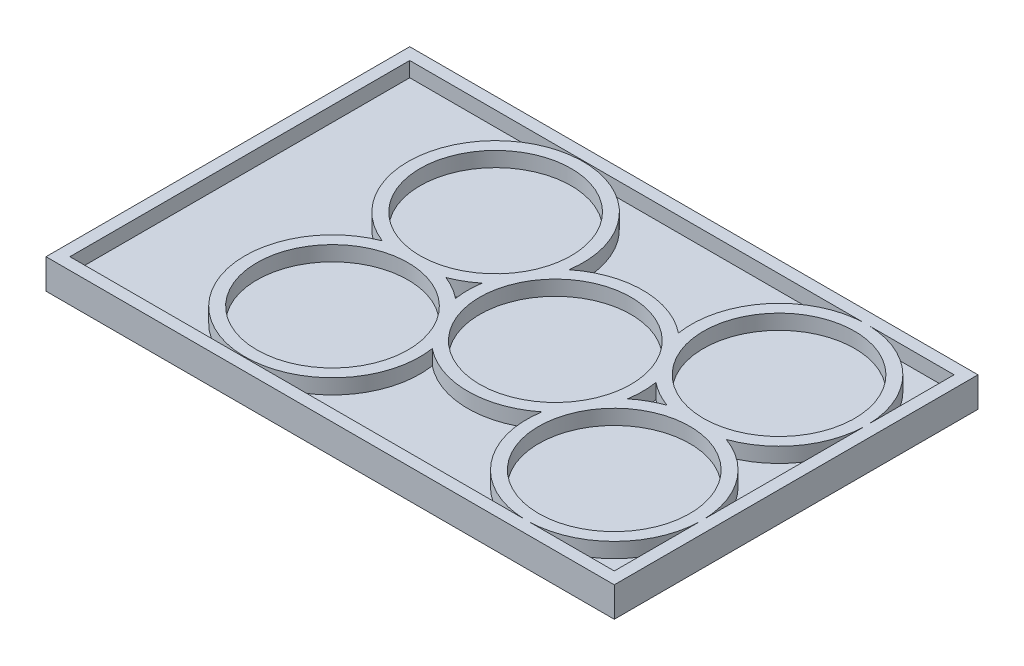
SolidWorks part; units mm, degrees
ref_plane "Front Plane" through (0, 0, 0) normal (0, 0, 1) x (1, 0, 0)
ref_plane "Top Plane" through (0, 0, 0) normal (0, 1, 0) x (1, 0, 0)
ref_plane "Right Plane" through (0, 0, 0) normal (1, 0, 0) x (0, 0, -1)
sketch "Sketch1" plane through (0, 0, 0) normal (0, 1, 0) x (1, 0, 0)
  line L1 (-43.2038, 39.7322) -> (32.8362, 39.7322)
  line L2 (-43.2038, 39.7322) -> (-43.2038, -8.9378)
  line L3 (-43.2038, -8.9378) -> (32.8362, -8.9378)
  line L4 (32.8362, 39.7322) -> (32.8362, -8.9378)
extrude "Boss-Extrude1" add sketch "Sketch1" along normal blind 2
sketch "Sketch2" plane through (0, 2, 0) normal (0, 1, 0) x (1, 0, 0)
  line L0 (32.8362, 39.7322) -> (32.8362, 26.4222)
  line L1 (32.8362, -8.9378) -> (32.8362, 39.7322) construction
  line L3 (32.8362, -8.9378) -> (32.8362, 4.3722)
  line L8 (-43.2038, 39.7322) -> (-43.2038, 38.1322)
  line L9 (-43.2038, 39.7322) -> (32.8362, 39.7322)
  line L10 (-43.2038, 39.7322) -> (-43.2038, -8.9378)
  line L11 (-43.2038, -8.9378) -> (32.8362, -8.9378)
  line L12 (32.8362, 39.7322) -> (32.8362, -8.9378)
  line L14 (32.8362, -8.9378) -> (31.2362, -8.9378)
  line L17 (31.2362, -7.3378) -> (-41.6038, -7.3378)
  line L18 (31.2362, -7.3378) -> (31.2362, 38.1322)
  line L19 (31.2362, 38.1322) -> (-41.6038, 38.1322)
  line L20 (-41.6038, -7.3378) -> (-41.6038, 38.1322)
  circle A0 centre (19.5262, 26.4222) radius 10.115
  circle A1 centre (19.5262, 26.4222) radius 11.715
  circle A2 centre (19.5262, 4.3722) radius 10.115
  circle A4 centre (0.6157, 15.3972) radius 10.115
  circle A5 centre (0.6157, 15.3972) radius 11.715
  circle A6 centre (-18.2897, 26.3122) radius 10.115
  circle A7 centre (-18.2897, 26.3122) radius 11.715
  circle A8 centre (-18.2897, 4.4822) radius 10.115
  circle A9 centre (-18.2897, 4.4822) radius 11.715
  circle A10 centre (19.5262, 4.3722) radius 11.715
extrude "Boss-Extrude5" add sketch "Sketch2" along normal blind 2 contours A9 A6 A5 A7 | A5 A7 | A9 A7 A5 A6 | A7 A9 | A5 A9 A7 A8 | A5 A9 | A9 A4 A7 A5 | A10 A5 A1 A7 A4 A9 | A1 A5 | A10 A1 L18 L19 A5 A0 | A1 A10 | L17 A10 L18 A1 A5 A2 | A5 A10 | A7 A9 A5 A8
sketch "Sketch3" plane through (0, 2, 0) normal (0, 1, 0) x (1, 0, 0)
  line L0 (-43.2038, 39.7322) -> (-41.6038, 39.7322)
  line L1 (-43.2038, 39.7322) -> (32.8362, 39.7322)
  line L2 (-43.2038, 39.7322) -> (-43.2038, -8.9378)
  line L3 (-43.2038, -8.9378) -> (32.8362, -8.9378)
  line L4 (32.8362, 39.7322) -> (32.8362, -8.9378)
  line L6 (32.8362, -8.9378) -> (31.2362, -8.9378)
  line L9 (-41.6038, 38.1322) -> (31.2362, 38.1322)
  line L10 (-41.6038, 38.1322) -> (-41.6038, -7.3378)
  line L11 (-41.6038, -7.3378) -> (31.2362, -7.3378)
  line L12 (31.2362, 38.1322) -> (31.2362, -7.3378)
  point P10 (0, 0)
  line M13 (31.2362, 4.7144) -> (31.2362, 4.0299)
  line M15 (19.8684, -7.3378) -> (19.1839, -7.3378)
  line M22 (19.1839, 38.1322) -> (19.8684, 38.1322)
  line M24 (31.2362, 26.7644) -> (31.2362, 26.0799)
  line M25 (-43.2038, 39.7322) -> (-43.2038, -8.9378)
  line M26 (-43.2038, -8.9378) -> (32.8362, -8.9378)
  line M27 (32.8362, -8.9378) -> (32.8362, 39.7322)
  line M28 (32.8362, 39.7322) -> (-43.2038, 39.7322)
extrude "Boss-Extrude6" add sketch "Sketch3" along normal blind 2 contours L3 L9 L12 L11 L10 M28 M25 M26 M27 M24 M13 M15 M22
